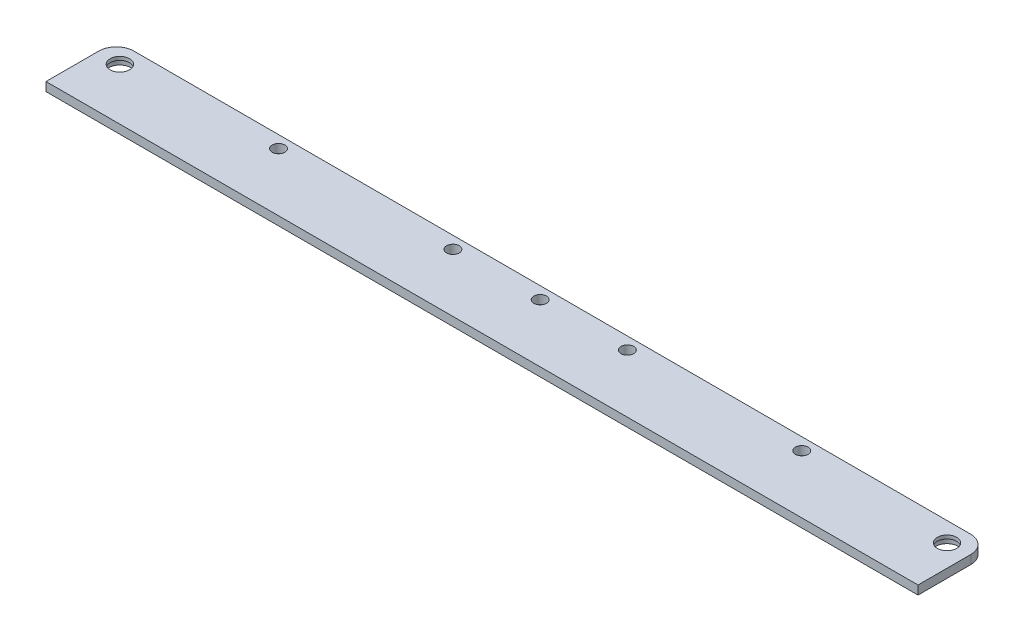
SolidWorks part; units mm, degrees
ref_plane "Front Plane" through (0, 0, 0) normal (0, 0, 1) x (1, 0, 0)
ref_plane "Top Plane" through (0, 0, 0) normal (0, 1, 0) x (1, 0, 0)
ref_plane "Right Plane" through (0, 0, 0) normal (1, 0, 0) x (0, 0, -1)
sketch "Sketch1" plane through (0, 0, 0) normal (0, 1, 0) x (1, 0, 0)
  line L1 (-392.299, 63.778) -> (103.701, 63.778)
  line L2 (-392.299, 63.778) -> (-392.299, 23.778)
  line L3 (-392.299, 23.778) -> (103.701, 23.778)
  line L4 (103.701, 63.778) -> (103.701, 23.778)
  line L8 (-379.799, 53.278) -> (-379.799, 63.778) construction
  line L9 (91.201, 52.778) -> (91.201, 63.778) construction
  line L10 (-144.299, 63.778) -> (-144.299, 183.778) construction
  line L14 (-392.299, 53.278) -> (-392.299, 63.778) construction
  line L15 (-199.299, 183.778) -> (-89.299, 183.778) construction
  line L18 (-392.299, 56.8447) -> (-293.099, 56.8447) construction
  line L20 (-293.099, 56.8447) -> (-193.899, 56.8447) construction
  line L22 (-193.899, 56.8447) -> (-94.699, 56.8447) construction
  line L23 (-94.699, 56.8447) -> (4.501, 56.8447) construction
  line L24 (4.501, 56.8447) -> (103.701, 56.8447) construction
  circle A5 centre (-379.799, 53.278) radius 5.5
  circle A6 centre (91.201, 52.778) radius 5.5
  circle A10 centre (-293.099, 56.8447) radius 3.6
  circle A11 centre (-193.899, 56.8447) radius 3.6
  circle A12 centre (-94.699, 56.8447) radius 3.6
  circle A13 centre (4.501, 56.8447) radius 3.6
  circle A14 centre (-144.299, 56.8447) radius 3.6
  point P24 (-144.299, 183.778)
  dimension "D5" = 11
  dimension "D6" = 10.5
  dimension "D7" = 11
  dimension "D3" = 12.5
  dimension "D8" = 11
  dimension "D9" = 7.2
  dimension "D10" = 7.2
  dimension "D11" = 99.2
  dimension "D13" = 7.2
  dimension "D4" = 7.2
  dimension "D15" = 7.2
  dimension "D1" = 496
  dimension "D2" = 40
  dimension "D12" = 471.0003
  dimension "D14" = 120
  dimension "D16" = 12.5
extrude "Boss-Extrude1" add sketch "Sketch1" along normal blind 5
sketch "Sketch2" plane through (0, 0, 0) normal (0, -1, 0) x (1, 0, 0)
  circle A0 centre (-379.799, -53.278) radius 6.5
  circle A1 centre (91.201, -52.778) radius 6.5
  dimension "D1" = 13
  dimension "D2" = 13
extrude "Cut-Extrude1" cut sketch "Sketch2" against normal blind 3
fillet "Fillet1" radius 10 2 edges at (103.701, 2.5, -63.778) (-392.299, 2.5, -63.778)
